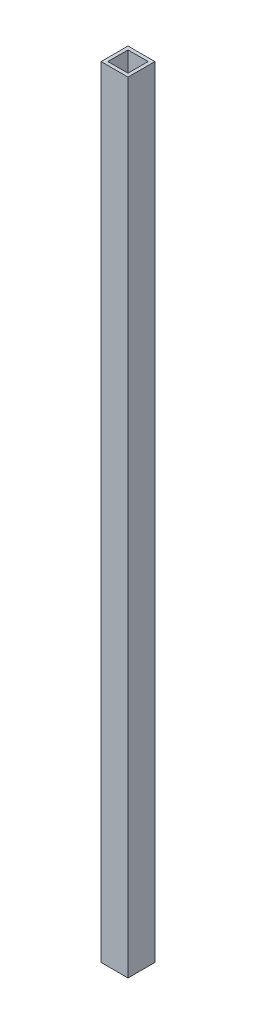
SolidWorks part; units mm, degrees
material "1060 Alloy"
ref_plane "Front Plane" through (0, 0, 0) normal (0, 0, 1) x (1, 0, 0)
ref_plane "Top Plane" through (0, 0, 0) normal (0, 1, 0) x (1, 0, 0)
ref_plane "Right Plane" through (0, 0, 0) normal (1, 0, 0) x (0, 0, -1)
sketch "Sketch1" plane through (0, 0, 0) normal (0, 1, 0) x (1, 0, 0)
  line L1 (0, 0) -> (25.4, 0)
  line L2 (0, 0) -> (0, 25.4)
  line L3 (0, 25.4) -> (25.4, 25.4)
  line L4 (25.4, 0) -> (25.4, 25.4)
  line L5 (3.175, 3.175) -> (22.225, 3.175)
  line L6 (3.175, 3.175) -> (3.175, 22.225)
  line L7 (3.175, 22.225) -> (22.225, 22.225)
  line L8 (22.225, 3.175) -> (22.225, 22.225)
  dimension "D1" = 25.4
  dimension "D2" = 25.4
  dimension "D3" = 3.175
  dimension "D4" = 3.175
  dimension "D5" = 3.175
  dimension "D6" = 3.175
extrude "Boss-Extrude1" add sketch "Sketch1" along normal blind 736.6
